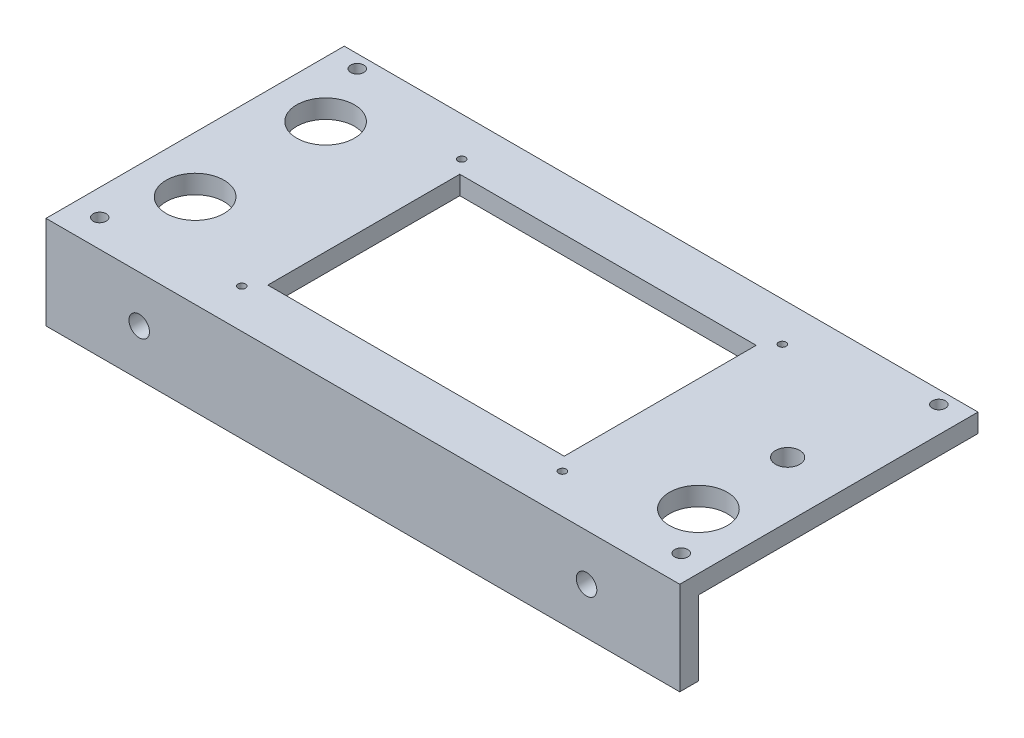
SolidWorks part; units mm, degrees
ref_plane "前视基准面" through (0, 0, 0) normal (0, 0, 1) x (1, 0, 0)
ref_plane "上视基准面" through (0, 0, 0) normal (0, 1, 0) x (1, 0, 0)
ref_plane "右视基准面" through (0, 0, 0) normal (1, 0, 0) x (0, 0, -1)
sketch "草图1" plane through (0, 0, 0) normal (0, 1, 0) x (1, 0, 0)
  line L1 (-27.8571, 29.4048) -> (142.1429, 29.4048)
  line L2 (-27.8571, 29.4048) -> (-27.8571, -50.5952)
  line L3 (-27.8571, -50.5952) -> (142.1429, -50.5952)
  line L4 (142.1429, 29.4048) -> (142.1429, -50.5952)
  line L5 (-27.8571, 29.4048) -> (142.1429, -50.5952) construction
  line L6 (-27.8571, -50.5952) -> (142.1429, 29.4048) construction
  point P4 (57.1429, -10.5952)
  dimension "D1" = 80
  dimension "D2" = 170
extrude "凸台-拉伸1" add sketch "草图1" along normal blind 5
sketch "草图2" plane through (0, 5, 0) normal (0, 1, 0) x (1, 0, 0)
  line L0 (-27.8571, -10.5952) -> (142.1429, -10.5952) construction
  line L1 (-27.8571, 29.4048) -> (-27.8571, -50.5952) construction
  line L2 (142.1429, -50.5952) -> (142.1429, 29.4048) construction
  line L3 (57.1429, 29.4048) -> (57.1429, -50.5952) construction
  line L4 (142.1429, 29.4048) -> (-27.8571, 29.4048) construction
  line L5 (-27.8571, -50.5952) -> (142.1429, -50.5952) construction
  line L7 (17.3929, 15.1548) -> (96.8929, 15.1548)
  line L8 (17.3929, 15.1548) -> (17.3929, -36.3452)
  line L9 (17.3929, -36.3452) -> (96.8929, -36.3452)
  line L10 (96.8929, 15.1548) -> (96.8929, -36.3452)
  line L11 (57.1429, -36.3452) -> (57.1429, 15.1548) construction
  line L12 (17.3929, -10.5952) -> (96.8929, -10.5952) construction
  circle A0 centre (-12.8571, 9.4048) radius 7.75
  circle A1 centre (-12.8571, -25.5952) radius 7.75
  circle A2 centre (127.1429, -6.6596) radius 3.25
  circle A3 centre (127.1429, -30.5952) radius 7.75
  point P12 (57.1429, -10.5952)
  dimension "D3" = 15.5
  dimension "D8" = 6.5
  dimension "D9" = 15.5
  dimension "D1" = 79.5
  dimension "D2" = 51.5
  dimension "D4" = 20
  dimension "D5" = 15
  dimension "D6" = 35
  dimension "D7" = 15
  dimension "D10" = 15
  dimension "D11" = 15
extrude "切除-拉伸1" cut sketch "草图2" against normal through all
sketch "草图3" plane through (-27.8571, 0, 0) normal (-1, 0, 0) x (0, 0, 1)
  line L1 (-29.4048, 5) -> (50.5952, 5)
  line L2 (-29.4048, 5) -> (-29.4048, -20)
  line L3 (-29.4048, -20) -> (50.5952, -20)
  line L4 (50.5952, 5) -> (50.5952, -20)
  line L5 (-29.4048, 5) -> (50.5952, -20) construction
  line L6 (-29.4048, -20) -> (50.5952, 5) construction
  point P4 (10.5952, -7.5)
  dimension "D1" = 25
sketch "草图5" plane through (0, 0, 50.5952) normal (0, 0, -1) x (-1, 0, 0)
  line L0 (27.8571, 5) -> (27.8571, -20) construction
  line L1 (-142.1429, 5) -> (27.8571, 5)
  line L2 (-142.1429, 5) -> (-142.1429, -20)
  line L3 (-142.1429, -20) -> (27.8571, -20)
  line L4 (27.8571, 5) -> (27.8571, -20)
  line L5 (-142.1429, 5) -> (27.8571, -20) construction
  line L6 (-142.1429, -20) -> (27.8571, 5) construction
  point P4 (-57.1429, -7.5)
  dimension "D1" = 25
extrude "凸台-拉伸3" add sketch "草图5" along normal blind 5
sketch "草图7" plane through (0, 0, 50.5952) normal (0, 0, 1) x (1, 0, 0)
  line L0 (-27.8571, -7.5) -> (142.1429, -7.5) construction
  line L1 (142.1429, 5) -> (142.1429, -20) construction
  line L2 (-27.8571, 5) -> (-27.8571, -20) construction
  circle A0 centre (-2.8571, -7.5) radius 2.75
  circle A1 centre (117.1429, -7.5) radius 2.75
  dimension "D2" = 5.5
  dimension "D3" = 5.5
  dimension "D1" = 25
  dimension "D4" = 25
extrude "切除-拉伸4" cut sketch "草图7" against normal through all
ref_plane "基准面1" through (-27.8571, 0, -29.4048) normal (-1, 0, 0) x (0, 0, 1)
sketch "草图9" plane through (0, 0, 0) normal (0, -1, 0) x (1, 0, 0)
  circle A0 centre (14.1429, -18.9048) radius 1
  circle A1 centre (100.1429, -18.9048) radius 1
  circle A2 centre (100.1429, 40.0952) radius 1
  circle A3 centre (14.1429, 40.0952) radius 1
extrude "切除-拉伸5" cut sketch "草图9" against normal through all
sketch "草图10" plane through (0, 5, 0) normal (0, 1, 0) x (1, 0, 0)
  line L0 (57.1429, 29.4048) -> (57.1429, -50.5952) construction
  line L1 (142.1429, 29.4048) -> (-27.8571, 29.4048) construction
  line L2 (-27.8571, -50.5952) -> (142.1429, -50.5952) construction
  line L3 (-20.8571, 25.9048) -> (-20.8571, -43.1914) construction
  line L4 (-27.8571, 29.4048) -> (-27.8571, -50.5952) construction
  circle A0 centre (-20.8571, 25.9048) radius 1.75
  circle A1 centre (-20.8571, -43.1914) radius 1.75
  circle A2 centre (135.1429, -43.1914) radius 1.75
  circle A3 centre (135.1429, 25.9048) radius 1.75
  dimension "D2" = 3.5
  dimension "D3" = 3.5
  dimension "D1" = 7
  dimension "D4" = 3.5
extrude "切除-拉伸6" cut sketch "草图10" against normal through all
